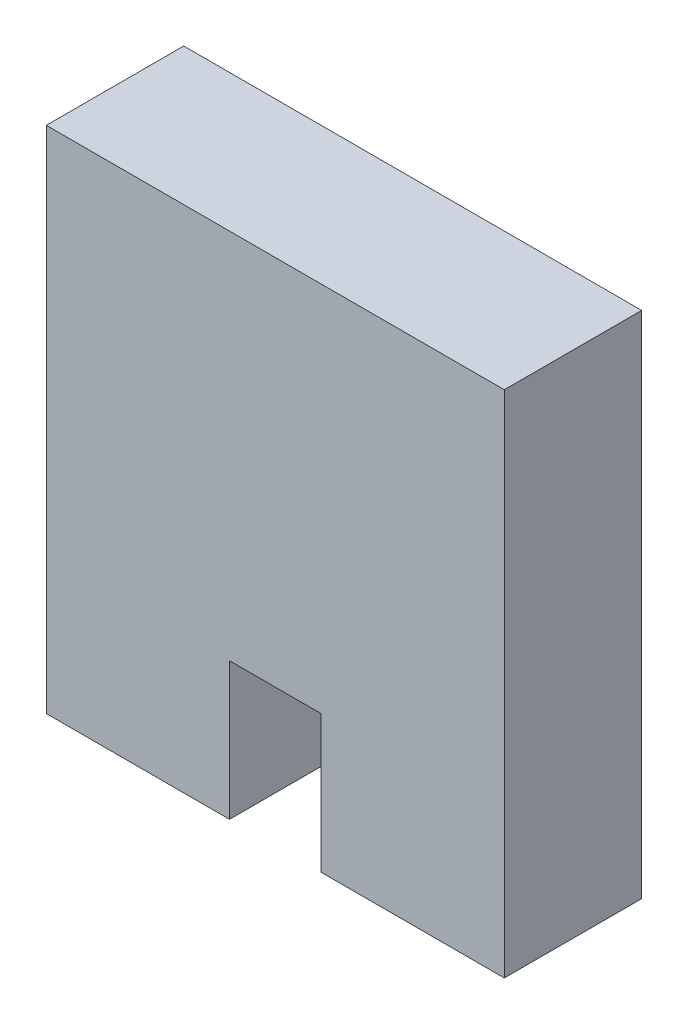
SolidWorks part; units mm, degrees
ref_plane "Plan de face" through (0, 0, 0) normal (0, 0, 1) x (1, 0, 0)
ref_plane "Plan de dessus" through (0, 0, 0) normal (0, 1, 0) x (1, 0, 0)
ref_plane "Plan de droite" through (0, 0, 0) normal (1, 0, 0) x (0, 0, -1)
sketch "Esquisse1" plane through (0, 0, 0) normal (0, 0, 1) x (1, 0, 0)
  line L0 (0, 0) -> (0, 22.25)
  line L1 (0, 22.25) -> (-20, 22.25)
  line L2 (-20, 22.25) -> (-20, 0)
  line L3 (-20, 0) -> (-12, 0)
  line L4 (-12, 0) -> (-12, 6)
  line L5 (-12, 6) -> (-8, 6)
  line L6 (-8, 6) -> (-8, 0)
  line L7 (-8, 0) -> (0, 0)
  dimension "D1" = 6
  dimension "D2" = 16.25
  dimension "D3" = 20
  dimension "D4" = 4
extrude "Boss.-Extru.1" add sketch "Esquisse1" along normal blind 6
